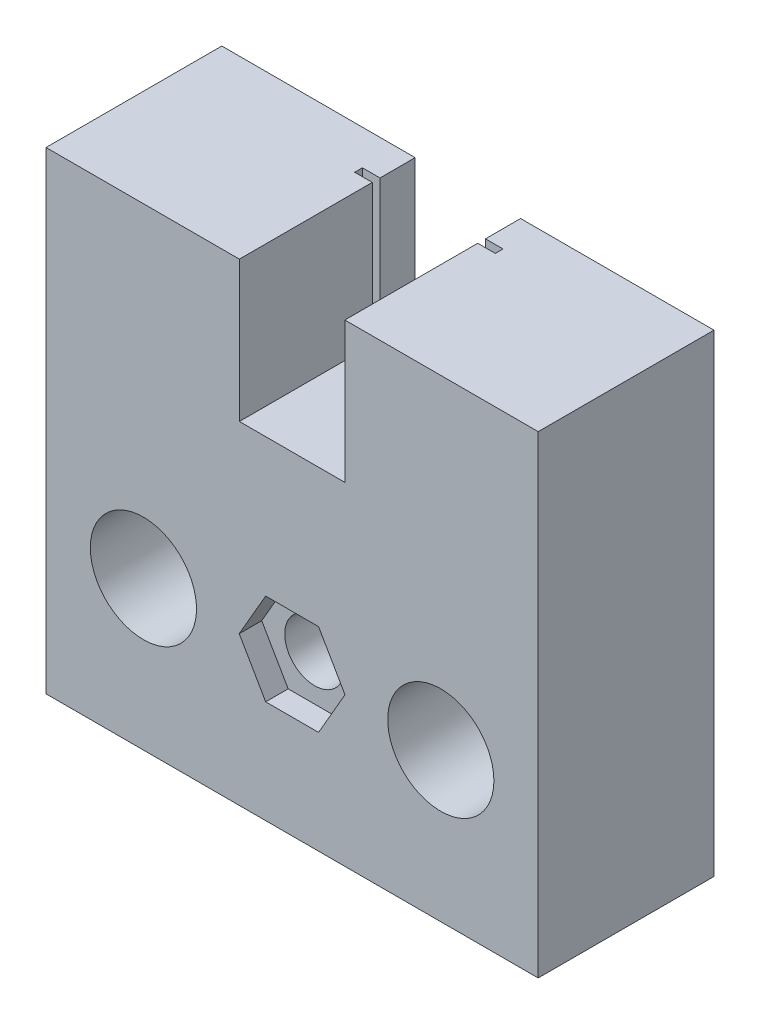
SolidWorks part; units mm, degrees
ref_plane "Front Plane" through (0, 0, 0) normal (0, 0, 1) x (1, 0, 0)
ref_plane "Top Plane" through (0, 0, 0) normal (0, 1, 0) x (1, 0, 0)
ref_plane "Right Plane" through (0, 0, 0) normal (1, 0, 0) x (0, 0, -1)
sketch "Sketch1" plane through (0, 0, 0) normal (0, 0, 1) x (1, 0, 0)
  line L0 (-3.8433, 42.2535) -> (31.1567, 42.2535)
  line L5 (31.1567, 42.2535) -> (31.1567, -25.0465)
  line L6 (31.1567, -25.0465) -> (-4.7053, -25.0465)
  line L7 (-3.8433, 42.2535) -> (-38.8433, 42.2535)
  line L8 (-38.8433, 42.2535) -> (-38.8433, -25.0465)
  line L9 (-38.8433, -25.0465) -> (-4.7053, -25.0465)
  dimension "D3" = 35
  dimension "D4" = 35
  dimension "D5" = 67.3
extrude "Boss-Extrude1" add sketch "Sketch1" along normal blind 25
sketch "Sketch2" plane through (0, 0, 25) normal (0, 0, 1) x (1, 0, 0)
  line L1 (3.6796, -3.8965) -> (-0.0819, 2.6185)
  line L2 (-0.0819, 2.6185) -> (-7.6048, 2.6185)
  line L3 (-7.6048, 2.6185) -> (-11.3662, -3.8965)
  line L4 (-11.3662, -3.8965) -> (-7.6048, -10.4115)
  line L5 (-7.6048, -10.4115) -> (-0.0819, -10.4115)
  line L6 (-0.0819, -10.4115) -> (3.6796, -3.8965)
  circle A0 centre (-3.8433, -3.8965) radius 6.515 construction
  dimension "D1" = 13.03
extrude "Cut-Extrude1" cut sketch "Sketch2" against normal blind 3.2
sketch "Sketch3" plane through (0, 0, 0) normal (0, 0, -1) x (-1, 0, 0)
  line L1 (11.3662, -3.8965) -> (7.6048, 2.6185)
  line L2 (7.6048, 2.6185) -> (0.0819, 2.6185)
  line L3 (0.0819, 2.6185) -> (-3.6796, -3.8965)
  line L4 (-3.6796, -3.8965) -> (0.0819, -10.4115)
  line L5 (0.0819, -10.4115) -> (7.6048, -10.4115)
  line L6 (7.6048, -10.4115) -> (11.3662, -3.8965)
  circle A0 centre (3.8433, -3.8965) radius 6.515 construction
  dimension "D1" = 13.03
extrude "Cut-Extrude2" cut sketch "Sketch3" against normal blind 3.2
sketch "Sketch4" plane through (0, 0, 21.8) normal (0, 0, 1) x (1, 0, 0)
  circle A0 centre (-3.8433, -3.8965) radius 4.25
  dimension "D1" = 8.5
extrude "Cut-Extrude3" cut sketch "Sketch4" against normal through all both and the other way through all
sketch "Sketch5" plane through (0, 0, 25) normal (0, 0, 1) x (1, 0, 0)
  circle A0 centre (17.3067, -3.8965) radius 7.55
  circle A1 centre (-24.9933, -3.8965) radius 7.55
  dimension "D2" = 15.1
extrude "Cut-Extrude4" cut sketch "Sketch5" against normal through all both
sketch "Sketch6" plane through (0, 42.2535, 0) normal (0, 1, 0) x (1, 0, 0)
  line L0 (-3.8433, 0) -> (3.6567, 0)
  line L1 (31.1567, 0) -> (-38.8433, 0) construction
  line L3 (31.1567, -25) -> (-38.8433, -25) construction
  line L4 (3.6567, -25) -> (-11.3433, -25)
  line L5 (-3.8433, 0) -> (-11.3433, 0)
  line L7 (3.6567, 0) -> (3.6567, -5)
  line L8 (3.6567, -5) -> (6.1567, -5)
  line L9 (6.1567, -5) -> (6.1567, -6.1)
  line L10 (6.1567, -6.1) -> (3.6567, -6.1)
  line L11 (3.6567, -6.1) -> (3.6567, -25)
  line L13 (-11.3433, 0) -> (-11.3433, -5)
  line L14 (-11.3433, -6.1) -> (-11.3433, -25)
  line L15 (-13.8433, -6.1) -> (-11.3433, -6.1)
  line L16 (-13.8433, -5) -> (-13.8433, -6.1)
  line L17 (-11.3433, -5) -> (-13.8433, -5)
  dimension "D1" = 7.5
  dimension "D2" = 15
  dimension "D3" = 7.5
  dimension "D4" = 5
  dimension "D5" = 2.5
  dimension "D6" = 1.1
extrude "Cut-Extrude5" cut sketch "Sketch6" against normal blind 20
